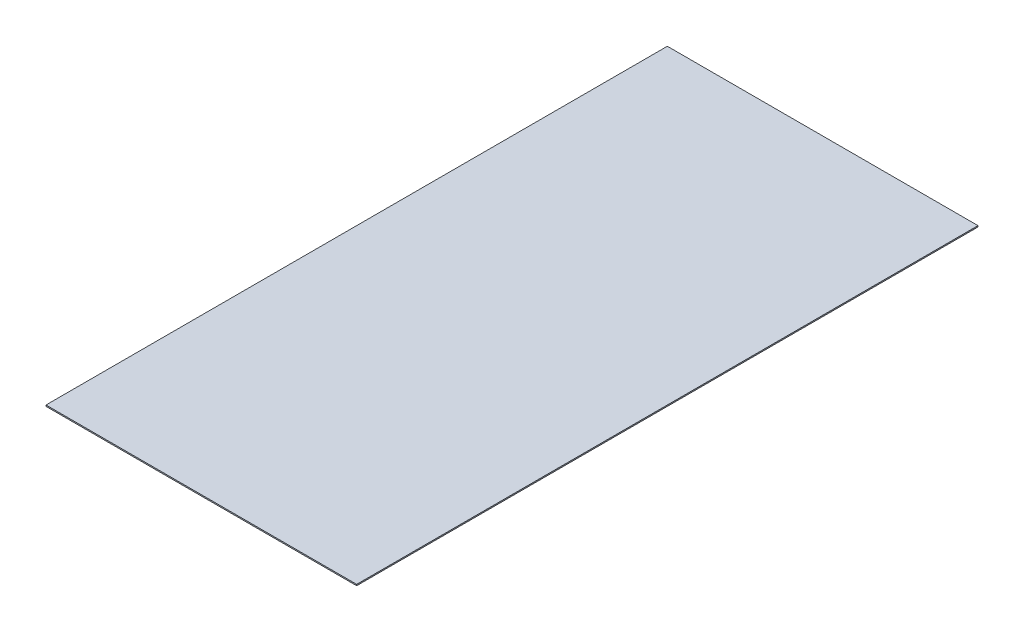
SolidWorks part; units mm, degrees
material "ASTM A36 Acero"
ref_plane "Alzado" through (0, 0, 0) normal (0, 0, 1) x (1, 0, 0)
ref_plane "Planta" through (0, 0, 0) normal (0, 1, 0) x (1, 0, 0)
ref_plane "Vista lateral" through (0, 0, 0) normal (1, 0, 0) x (0, 0, -1)
sketch "Croquis1" plane through (0, 0, 0) normal (0, 1, 0) x (1, 0, 0)
  line L1 (-609.6, -1219.2) -> (609.6, -1219.2)
  line L2 (-609.6, -1219.2) -> (-609.6, 1219.2)
  line L3 (-609.6, 1219.2) -> (609.6, 1219.2)
  line L4 (609.6, -1219.2) -> (609.6, 1219.2)
  line L5 (-609.6, -1219.2) -> (609.6, 1219.2) construction
  line L6 (-609.6, 1219.2) -> (609.6, -1219.2) construction
  point P0 (0, 0)
  dimension "D1" = 2438.4
  dimension "D2" = 1219.2
extrude "Saliente-Extruir1" add sketch "Croquis1" along normal blind 4.8
